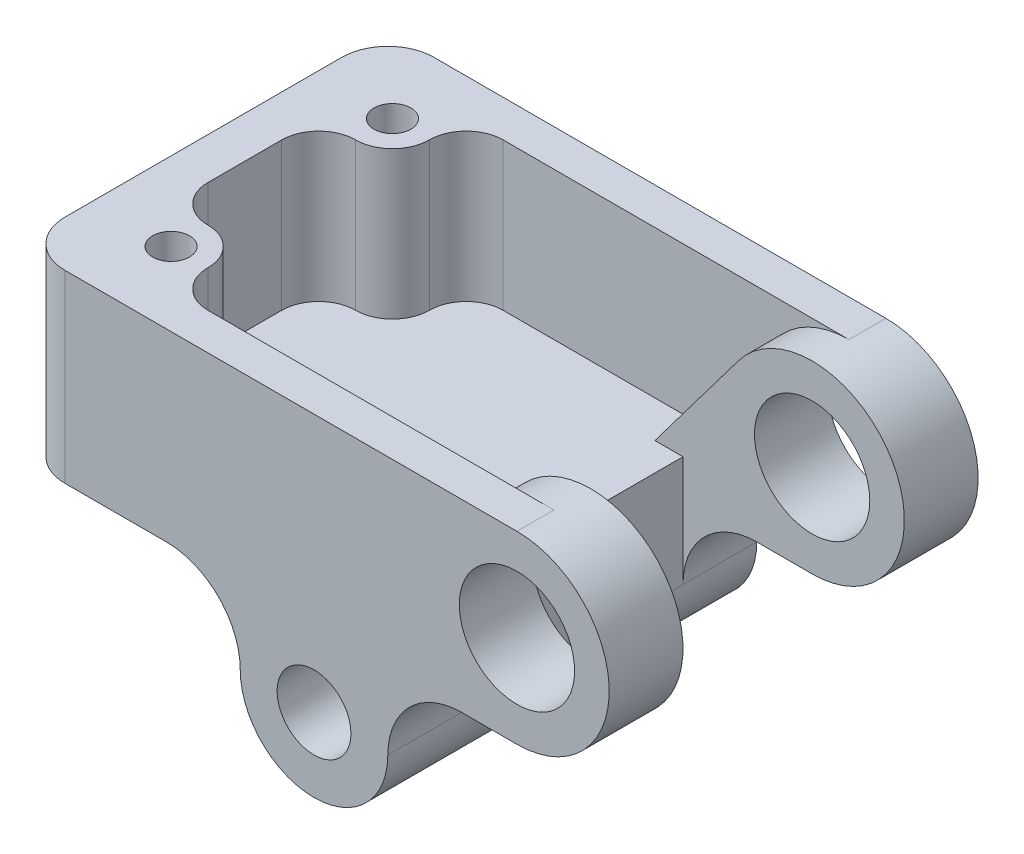
SolidWorks part; units mm, degrees
ref_plane "Front Plane" through (0, 0, 0) normal (0, 0, 1) x (1, 0, 0)
ref_plane "Top Plane" through (0, 0, 0) normal (0, 1, 0) x (1, 0, 0)
ref_plane "Right Plane" through (0, 0, 0) normal (1, 0, 0) x (0, 0, -1)
sketch "Sketch1" plane through (0, 0, 0) normal (0, 0, 1) x (1, 0, 0)
  line L0 (0, 0) -> (0, 48570.1759) construction
  line L1 (0, 0) -> (48570.1759, 0) construction
  line L2 (-64, 56) -> (-64, 16)
  line L3 (-64, 16) -> (-32, 16)
  line L4 (32, 16) -> (44, 16)
  line L5 (44, 56) -> (-64, 56)
  arc A0 (-32, 16) -> (-16, 0) centre (-32, 0) cw
  arc A1 (-16, 0) -> (16, 0) centre (0, 0) ccw
  arc A2 (16, 0) -> (32, 16) centre (32, 0) cw
  arc A3 (44, 16) -> (44, 56) centre (44, 36) ccw
  circle A4 centre (0, 0) radius 8
  circle A5 centre (44, 36) radius 12.5
  point P18 (44, 11.9277)
  point P19 (0, 0)
  point P21 (38, 16)
  point P22 (64, 36)
  dimension "D1" = 20
  dimension "D3" = 16
  dimension "D6" = 16
  dimension "D7" = 25
  dimension "D2" = 16
  dimension "D4" = 44
  dimension "D5" = 128
extrude "Boss-Extrude1" add sketch "Sketch1" along normal mid plane 80
sketch "Sketch2" plane through (0, 56, 0) normal (0, 1, 0) x (1, 0, 0)
  line L0 (64, 32) -> (-31, 32)
  line L1 (0, 0) -> (50000, 0) construction
  line L2 (64, -32) -> (-31, -32)
  line L3 (-55, 8) -> (-55, -8)
  line L4 (44, 40) -> (-64, 40) construction
  line L5 (-64, -40) -> (-64, 40) construction
  line L6 (64, 32) -> (64, -32)
  line L7 (64, -40) -> (64, 40) construction
  arc A0 (-31, 32) -> (-39, 24) centre (-31, 24) ccw
  arc A1 (-39, 24) -> (-47, 16) centre (-47, 24) cw
  arc A2 (-47, 16) -> (-55, 8) centre (-47, 8) ccw
  arc A3 (-47, -16) -> (-55, -8) centre (-47, -8) cw
  arc A4 (-39, -24) -> (-47, -16) centre (-47, -24) ccw
  arc A5 (-31, -32) -> (-39, -24) centre (-31, -24) cw
  point P0 (0, 0)
  dimension "D1" = 8
  dimension "D3" = 8
  dimension "D2" = 9
extrude "Cut-Extrude1" cut sketch "Sketch2" against normal blind 32
sketch "Sketch3" plane through (0, 24, 0) normal (0, 1, 0) x (1, 0, 0)
  line L0 (-31, -32) -> (40.5, -32) construction
  line L1 (60, 32) -> (16, 32)
  line L2 (60, 32) -> (60, -32)
  line L3 (60, -32) -> (16, -32)
  line L4 (16, 32) -> (16, -32)
  line L5 (16, -40) -> (16, 40) construction
extrude "Cut-Extrude2" cut sketch "Sketch3" against normal blind 32
sketch "Sketch4" plane through (0, 0, -32) normal (0, 0, 1) x (1, 0, 0)
  line L0 (28.0273, 48.0363) -> (9.9146, 24)
  line L1 (16, 24) -> (-31, 24) construction
  line L7 (44, 56) -> (-31, 56)
  line L8 (-31, 56) -> (-31, 24)
  line L9 (-31, 24) -> (16, 24)
  line L10 (16, 24) -> (16, 0)
  line L11 (32, 16) -> (44, 16)
  line L14 (9.9146, 24) -> (16, 24)
  line L15 (16, 24) -> (16, 0)
  line L16 (32, 16) -> (44, 16)
  circle A0 centre (44, 36) radius 20
  circle A1 centre (44, 36) radius 12.5 construction
  circle A2 centre (44, 36) radius 12.5
  arc A3 (32, 16) -> (16, 0) centre (32, 0) ccw
  arc A4 (44, 16) -> (44, 56) centre (44, 36) ccw
  arc A5 (32, 16) -> (16, 0) centre (32, 0) ccw
  arc A6 (44, 16) -> (44, 56) centre (44, 36) ccw
  point P5 (0, 0)
  circle M9 centre (44, 36) radius 12.5
  line M12 (-31, 24) -> (16, 24)
  line M13 (16, 24) -> (16, 0)
  arc M14 (16, 0) -> (32, 16) centre (32, 0) cw
  line M15 (32, 16) -> (44, 16)
  arc M16 (44, 16) -> (44, 56) centre (44, 36) ccw
  dimension "D1" = 40
  dimension "D2" = 53
  dimension "D3" = 0
extrude "Boss-Extrude2" add sketch "Sketch4" along normal blind 8 contours A0 M16 M9 | A0 L0 M12 M13 M14 M15
mirror "Mirror1" about plane through (0, 0, 0) normal (0, 0, 1) of "Boss-Extrude2"
hole_wizard "Ø8.0mm Dowel Hole1" positions "3DSketch1" profile "Sketch5" hole size "Ø8.0" standard "ANSI Metric" end condition through all
sketch3d "3DSketch1"
  line L0 (-47, 24, -24) -> (-47, 56, -24) construction
  line L1 (-47, 24, 24) -> (-47, 56, 24) construction
  point P0 (-47, 56, -24)
  point P4 (-47, 56, 24)
sketch "Sketch5" plane through (-47, 56, -24) normal (1, 0, 0) x (0, 0, 1)
  line L0 (0, 0) -> (0, 72)
  line L1 (0, 72) -> (4, 72)
  line L2 (4, 72) -> (4, 0)
  line L5 (4, 0) -> (0, 0)
  line L11 (0, -6.35) -> (0, 107.95) construction
  dimension "Thru Hole Dia." = 8
  dimension "Thru Hole Depth" = 72
fillet "Fillet1" radius 10 2 edges at (-64, 36, -40) (-64, 36, 40)
sketch "Sketch6" plane through (-64, 0, 0) normal (-1, 0, 0) x (0, 0, 1)
  line L0 (-16, 16) -> (-16, 32)
  line L1 (30, 16) -> (-30, 16) construction
  line L2 (16, 32) -> (16, 16)
  line L3 (16, 16) -> (-16, 16)
  arc A0 (-16, 32) -> (16, 32) centre (0, 32) cw
  circle A1 centre (0, 32) radius 4
  dimension "D1" = 16
  dimension "D2" = 16
  dimension "D3" = 8
extrude "Boss-Extrude3" add sketch "Sketch6" along normal blind 8
